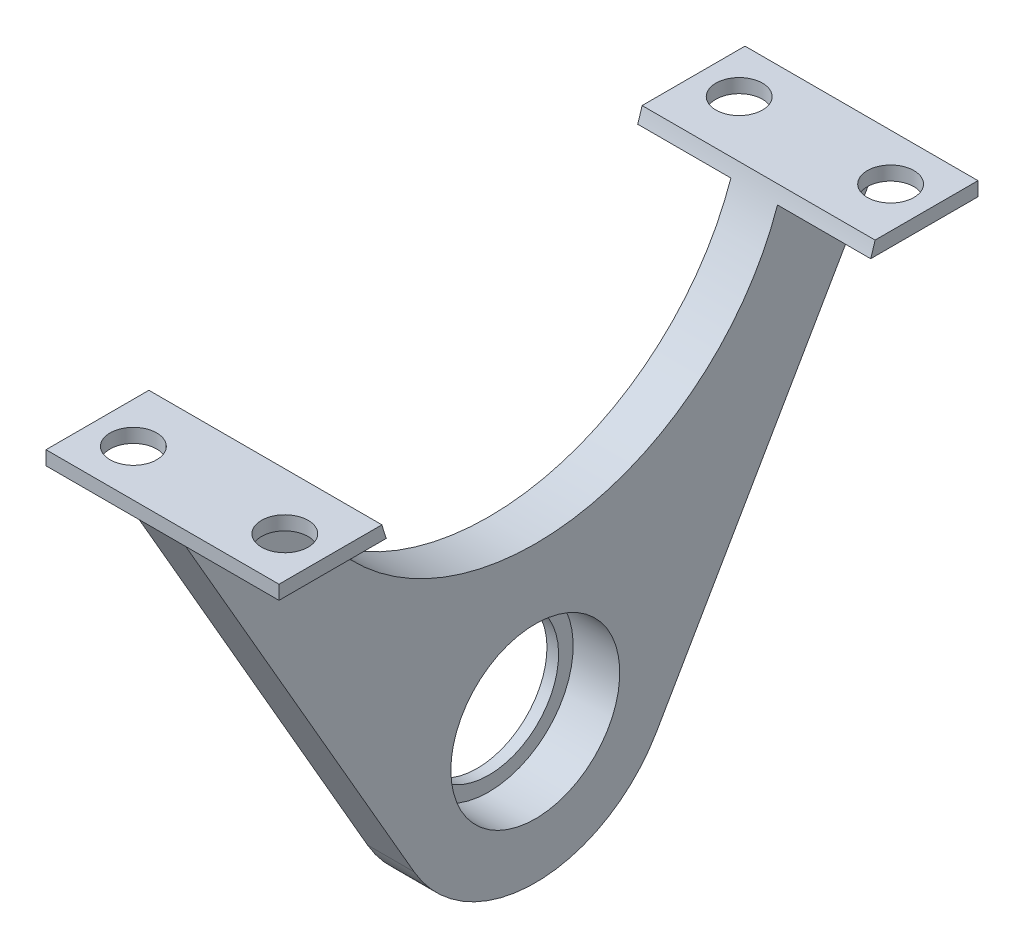
SolidWorks part; units mm, degrees
ref_plane "前视基准面" through (0, 0, 0) normal (0, 0, 1) x (1, 0, 0)
ref_plane "上视基准面" through (0, 0, 0) normal (0, 1, 0) x (1, 0, 0)
ref_plane "右视基准面" through (0, 0, 0) normal (1, 0, 0) x (0, 0, -1)
sketch "草图1" plane through (0, 0, 0) normal (0, 0, 1) x (1, 0, 0)
  line L0 (0, 0) -> (0, 40)
  line L1 (0, 40) -> (8, 40)
  line L2 (8, 40) -> (8, 41.2)
  line L3 (8, 41.2) -> (-12, 41.2)
  line L4 (-12, 41.2) -> (-12, 40)
  line L5 (-12, 40) -> (-4, 40)
  line L6 (-4, 40) -> (-4, 0)
  line L7 (-4, 0) -> (0, 0)
  dimension "D1" = 4
  dimension "D2" = 1.2
  dimension "D3" = 8
  dimension "D4" = 8
  dimension "D5" = 40
extrude "凸台-拉伸1" add sketch "草图1" along normal blind 60
sketch "草图2" plane through (0, 0, 0) normal (1, 0, 0) x (0, 0, -1)
  line L0 (-30, 0) -> (-30, 55.4065) construction
  line L1 (-60, 0) -> (0, 0) construction
  line L2 (-32, 12) -> (-8, 12) construction
  line L3 (-51.166, 41.2) -> (-8.834, 41.2)
  line L4 (-60, 41.2) -> (0, 41.2) construction
  line L5 (-60, 40) -> (-40.3952, 6.0051)
  line L6 (0, 40) -> (-19.6048, 6.0051)
  line L7 (0, 40) -> (0, 0)
  line L8 (0, 0) -> (-60, 0)
  line L9 (-60, 0) -> (-60, 40)
  circle A0 centre (-30, 12) radius 7.25
  arc A1 (-51.166, 41.2) -> (-8.834, 41.2) centre (-30, 47.2) ccw
  arc A2 (-40.3952, 6.0051) -> (-19.6048, 6.0051) centre (-30, 12) ccw
  line M6 (0, 0) -> (0, 40)
  line M8 (-60, 40) -> (-60, 0)
  line M9 (-60, 0) -> (0, 0)
  dimension "D1" = 12
  dimension "D2" = 14.5
  dimension "D3" = 22
  dimension "D4" = 6
extrude "切除-拉伸1" cut sketch "草图2" against normal blind 40 and the other way blind 40 contours A2 L8 L6 M6 | A2 L5 M8 M9 | A0 | L3 A1
sketch "草图3" plane through (-4, 0, 0) normal (-1, 0, 0) x (0, 0, 1)
  circle A0 centre (30, 12) radius 8
  circle A1 centre (30, 12) radius 6
  dimension "D1" = 12
  dimension "D2" = 16
extrude "凸台-拉伸2" add sketch "草图3" along normal blind 1
sketch "草图4" plane through (0, 40, 0) normal (0, -1, 0) x (1, 0, 0)
  line L0 (-2, 0) -> (-2, 60) construction
  line L1 (-4, 0) -> (0, 0) construction
  line L2 (-10, 4) -> (6, 4) construction
  line L5 (-2, 30) -> (-5, 30) construction
  line L6 (-5, 36) -> (-5, 24) construction
  circle A0 centre (-8.5, 4) radius 2
  circle A1 centre (4.5, 4) radius 2
  circle A2 centre (-8.5, 56) radius 2
  circle A3 centre (4.5, 56) radius 2
  point P20 (-2, 19.3335)
  point P21 (-5, 20)
  dimension "D1" = 4
  dimension "D2" = 13
  dimension "D3" = 52
extrude "切除-拉伸2" cut sketch "草图4" against normal up to next
